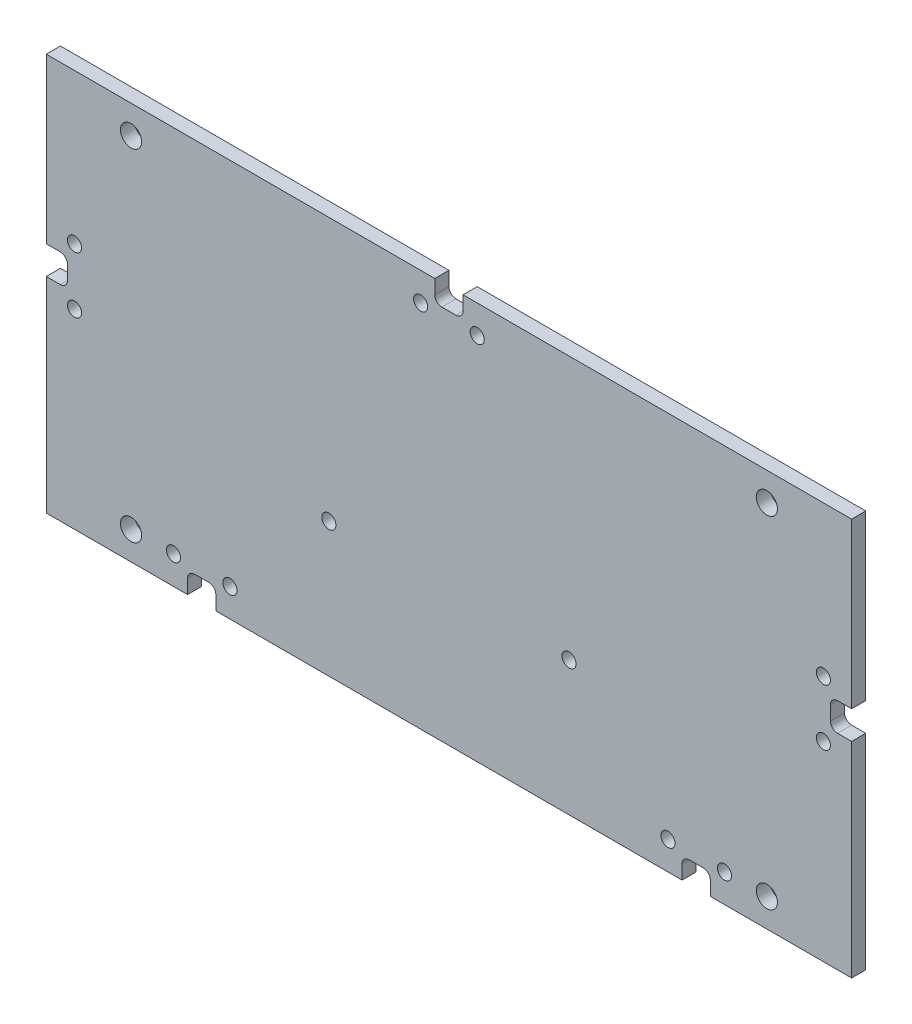
SolidWorks part; units mm, degrees
material "自訂玻璃纖維"
ref_plane "前基準面" through (0, 0, 0) normal (0, 0, 1) x (1, 0, 0)
ref_plane "上基準面" through (0, 0, 0) normal (0, 1, 0) x (1, 0, 0)
ref_plane "右基準面" through (0, 0, 0) normal (1, 0, 0) x (0, 0, -1)
sketch "草圖1" plane through (0, 0, 0) normal (0, 0, 1) x (1, 0, 0)
  line L0 (23.8615, 13.2435) -> (25.8615, 13.2435)
  line L1 (-31.1385, 16.2435) -> (22.8615, 16.2435)
  line L2 (-32.1385, 15.2435) -> (-32.1385, -7.0065)
  line L3 (-31.1385, -40.0065) -> (-12.1385, -40.0065)
  line L4 (81.8615, 15.2435) -> (81.8615, -7.0065)
  line L5 (-29.1385, -8.0065) -> (-29.1385, -10.0065)
  line L6 (22.8615, 16.2435) -> (22.8615, 14.2435)
  line L7 (26.8615, 16.2435) -> (80.8615, 16.2435)
  line L8 (26.8615, 16.2435) -> (26.8615, 14.2435)
  line L9 (-32.1385, -7.0065) -> (-30.1385, -7.0065)
  line L10 (81.8615, -11.0065) -> (81.8615, -39.0065)
  line L11 (-32.1385, -11.0065) -> (-30.1385, -11.0065)
  line L12 (-32.1385, -11.0065) -> (-32.1385, -39.0065)
  line L13 (81.8615, -11.0065) -> (79.8615, -11.0065)
  line L14 (81.8615, -7.0065) -> (79.8615, -7.0065)
  line L15 (78.8615, -8.0065) -> (78.8615, -10.0065)
  line L16 (-11.1385, -37.0065) -> (-9.1385, -37.0065)
  line L17 (58.8615, -37.0065) -> (60.8615, -37.0065)
  line L18 (-12.1385, -40.0065) -> (-12.1385, -38.0065)
  line L19 (-8.1385, -40.0065) -> (57.8615, -40.0065)
  line L20 (-8.1385, -40.0065) -> (-8.1385, -38.0065)
  line L21 (61.8615, -40.0065) -> (61.8615, -38.0065)
  line L22 (57.8615, -40.0065) -> (57.8615, -38.0065)
  line L23 (61.8615, -40.0065) -> (80.8615, -40.0065)
  line L24 (-31.1385, 16.2435) -> (-32.1385, 16.2435)
  line L25 (-32.1385, 16.2435) -> (-32.1385, 15.2435)
  line L26 (-32.1385, -39.0065) -> (-32.1385, -40.0065)
  line L27 (-32.1385, -40.0065) -> (-31.1385, -40.0065)
  line L28 (81.8615, -39.0065) -> (81.8615, -40.0065)
  line L29 (81.8615, -40.0065) -> (80.8615, -40.0065)
  line L30 (81.8615, 15.2435) -> (81.8615, 16.2435)
  line L31 (81.8615, 16.2435) -> (80.8615, 16.2435)
  circle A0 centre (55.8615, -36.0065) radius 1
  arc A1 (-30.1385, -7.0065) -> (-29.1385, -8.0065) centre (-30.1385, -8.0065) cw
  circle A2 centre (77.8615, -5.0065) radius 1
  circle A3 centre (-6.1385, -36.0065) radius 1
  circle A8 centre (28.8615, 12.2435) radius 1
  circle A9 centre (20.8615, 12.2435) radius 1
  arc A10 (22.8615, 14.2435) -> (23.8615, 13.2435) centre (23.8615, 14.2435) ccw
  arc A11 (25.8615, 13.2435) -> (26.8615, 14.2435) centre (25.8615, 14.2435) ccw
  circle A12 centre (-28.1385, -5.0065) radius 1
  circle A13 centre (-28.1385, -13.0065) radius 1
  circle A14 centre (77.8615, -13.0065) radius 1
  circle A15 centre (-14.1385, -36.0065) radius 1
  circle A16 centre (63.8615, -36.0065) radius 1
  arc A17 (-29.1385, -10.0065) -> (-30.1385, -11.0065) centre (-30.1385, -10.0065) cw
  arc A18 (78.8615, -10.0065) -> (79.8615, -11.0065) centre (79.8615, -10.0065) ccw
  arc A19 (79.8615, -7.0065) -> (78.8615, -8.0065) centre (79.8615, -8.0065) ccw
  arc A20 (-12.1385, -38.0065) -> (-11.1385, -37.0065) centre (-11.1385, -38.0065) cw
  arc A21 (-9.1385, -37.0065) -> (-8.1385, -38.0065) centre (-9.1385, -38.0065) cw
  arc A22 (57.8615, -38.0065) -> (58.8615, -37.0065) centre (58.8615, -38.0065) cw
  arc A23 (60.8615, -37.0065) -> (61.8615, -38.0065) centre (60.8615, -38.0065) cw
  point P14 (-32.1385, -40.0065)
  point P19 (81.8615, 16.2435)
  point P22 (-32.1385, 16.2435)
  dimension "D3" = 4
  dimension "D4" = 2
  dimension "D5" = 27
  dimension "D6" = 2
  dimension "D7" = 4
  dimension "D8" = 8
  dimension "D9" = 18
  dimension "D10" = 2
  dimension "D11" = 2
  dimension "D12" = 18
  dimension "D13" = 2
  dimension "D17" = 8
  dimension "D18" = 2
  dimension "D19" = 8
  dimension "D20" = 4
  dimension "D1" = 114
  dimension "D2" = 56.25
  dimension "D21" = 2
  dimension "D22" = 4
  dimension "D23" = 2
extrude "填料-伸長1" add sketch "草圖1" along normal blind 2
sketch "草圖2" plane through (0, 0, 2) normal (0, 0, 1) x (1, 0, 0)
  line L1 (-32.1385, -40.0065) -> (-12.1385, -40.0065) construction
  circle A0 centre (7.8615, -21.0065) radius 1
  circle A1 centre (41.8615, -21.0065) radius 1
  dimension "D1" = 19
  dimension "D2" = 19
  dimension "D3" = 2
extrude "除料-伸長1" cut sketch "草圖2" against normal blind 10
sketch "草圖3" plane through (0, 0, 2) normal (0, 0, 1) x (1, 0, 0)
  line L0 (-32.1385, -40.0065) -> (-12.1385, -40.0065) construction
  line L1 (-8.1385, -40.0065) -> (57.8615, -40.0065) construction
  line L2 (22.8615, 16.2435) -> (-32.1385, 16.2435) construction
  circle A0 centre (-20.1385, -36.0065) radius 1.5
  circle A1 centre (-20.1385, 12.2435) radius 1.5
  circle A2 centre (69.8615, 12.2435) radius 1.5
  circle A3 centre (69.8615, -36.0065) radius 1.5
  point P6 (24.8615, -40.0065)
  dimension "D1" = 3
  dimension "D2" = 4
  dimension "D3" = 45
  dimension "D4" = 4
  dimension "D5" = 48.25
extrude "除料-伸長2" cut sketch "草圖3" against normal blind 10
